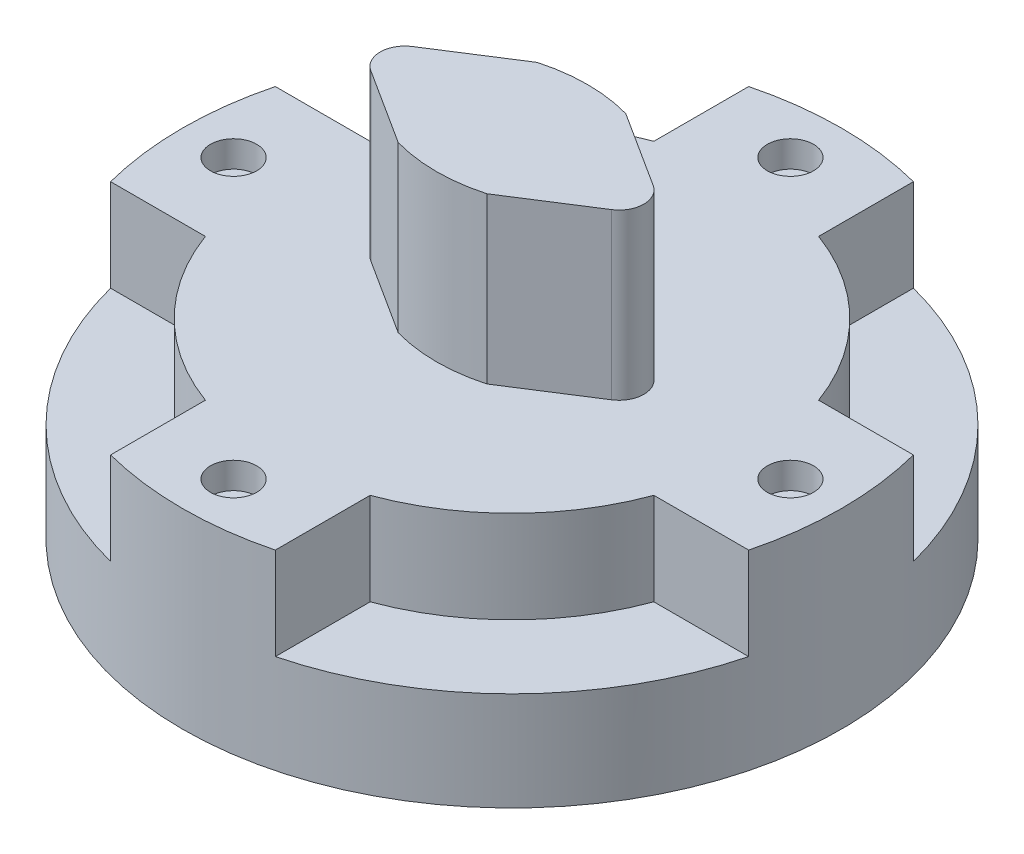
SolidWorks part; units mm, degrees
ref_plane "Front Plane" through (0, 0, 0) normal (0, 0, 1) x (1, 0, 0)
ref_plane "Top Plane" through (0, 0, 0) normal (0, 1, 0) x (1, 0, 0)
ref_plane "Right Plane" through (0, 0, 0) normal (1, 0, 0) x (0, 0, -1)
sketch "Sketch2" plane through (0, 0, 0) normal (0, 1, 0) x (1, 0, 0)
  circle A0 centre (0, 0) radius 100
  circle A1 centre (0, 0) radius 84.5 construction
  circle A2 centre (0, 84.5) radius 4.25
  circle A3 centre (84.5, 0) radius 4.25
  circle A4 centre (0, -84.5) radius 4.25
  circle A5 centre (-84.5, 0) radius 4.25
  point P15 (0, 0)
  dimension "D1" = 200
  dimension "D2" = 4
  dimension "D3" = 8.5
  dimension "D4" = 169
extrude "Boss-Extrude1" add sketch "Sketch2" along normal blind 58
sketch "Sketch3" plane through (0, 58, 0) normal (0, 1, 0) x (1, 0, 0)
  circle A0 centre (0, 84.5) radius 7
  circle A1 centre (84.5, 0) radius 7
  circle A2 centre (0, -84.5) radius 7
  circle A3 centre (-84.5, 0) radius 7
  circle A4 centre (0, 0) radius 100 construction
  point P12 (0, 0)
  dimension "D1" = 4
  dimension "D2" = 14
  dimension "D3" = 84.5
extrude "Cut-Extrude1" cut sketch "Sketch3" against normal blind 8
sketch "Sketch4" plane through (0, 58, 0) normal (0, 1, 0) x (1, 0, 0)
  line L0 (96.8246, 25) -> (68.0533, 25)
  line L2 (-96.8246, -25) -> (-68.0533, -25)
  line L6 (25, -96.8246) -> (25, -68.0533)
  line L8 (-68.0533, 25) -> (-96.8246, 25)
  line L9 (-96.8246, -25) -> (-68.3728, -25)
  line L10 (96.8246, 25) -> (68.0533, 25)
  line L11 (68.0533, -25) -> (96.8246, -25)
  line L12 (68.0533, -25) -> (96.8246, -25)
  line L13 (-25, 96.8246) -> (-25, 68.0533)
  line L14 (25, 68.0533) -> (25, 96.8246)
  line L15 (25, 68.0533) -> (25, 96.8246)
  line L17 (-68.0533, 25) -> (-96.8246, 25)
  line L18 (25, -68.0533) -> (25, -96.8246)
  line L19 (-25, -96.8246) -> (-25, -68.0533)
  line L20 (-25, -68.0533) -> (-25, -96.8246)
  arc A0 (-25, 68.0533) -> (-68.0533, 25) centre (0, 0) ccw
  circle A1 centre (0, 0) radius 100 construction
  circle A2 centre (0, 0) radius 100
  arc A3 (68.0533, 25) -> (25, 68.0533) centre (0, 0) ccw
  arc A4 (-68.0533, -25) -> (-25, -68.0533) centre (0, 0) ccw
  arc A5 (25, -68.0533) -> (68.0533, -25) centre (0, 0) ccw
  circle M16 centre (0, 0) radius 100
  dimension "D1" = 145
  dimension "D2" = 50
  dimension "D3" = 50
extrude "Cut-Extrude2" cut sketch "Sketch4" against normal blind 28 contours A0 L13 L8 M16 | A3 L0 L14 M16 | A5 L6 L11 M16 | A4 L2 L19 M16
sketch "Sketch5" plane through (0, 58, 0) normal (0, 1, 0) x (1, 0, 0)
  line L0 (0, 0) -> (0, 16.1283) construction
  line L1 (-84.5, 0) -> (84.5, 0) construction
  line L6 (-36.5385, 6.3199) -> (-13.4615, 21.0663)
  line L12 (13.4615, 21.0663) -> (36.5385, 6.3199)
  line L14 (13.4615, -21.0663) -> (36.5385, -6.3199)
  line L15 (-36.5385, -6.3199) -> (-13.4615, -21.0663)
  circle A0 centre (0, 0) radius 25 construction
  arc A1 (36.5385, -6.3199) -> (36.5385, 6.3199) centre (32.5, 0) ccw construction
  arc A2 (-36.5385, -6.3199) -> (-36.5385, 6.3199) centre (-32.5, 0) cw construction
  arc A5 (-13.4615, 21.0663) -> (13.4615, 21.0663) centre (0, -27.0875) cw
  arc A6 (-13.4615, -21.0663) -> (13.4615, -21.0663) centre (0, 27.0875) ccw
  arc A7 (-36.5385, -6.3199) -> (-36.5385, 6.3199) centre (-32.5, 0) cw
  arc A8 (36.5385, -6.3199) -> (36.5385, 6.3199) centre (32.5, 0) ccw
  dimension "D1" = 50
  dimension "D2" = 15
  dimension "D3" = 50
extrude "Boss-Extrude2" add sketch "Sketch5" along normal blind 50
